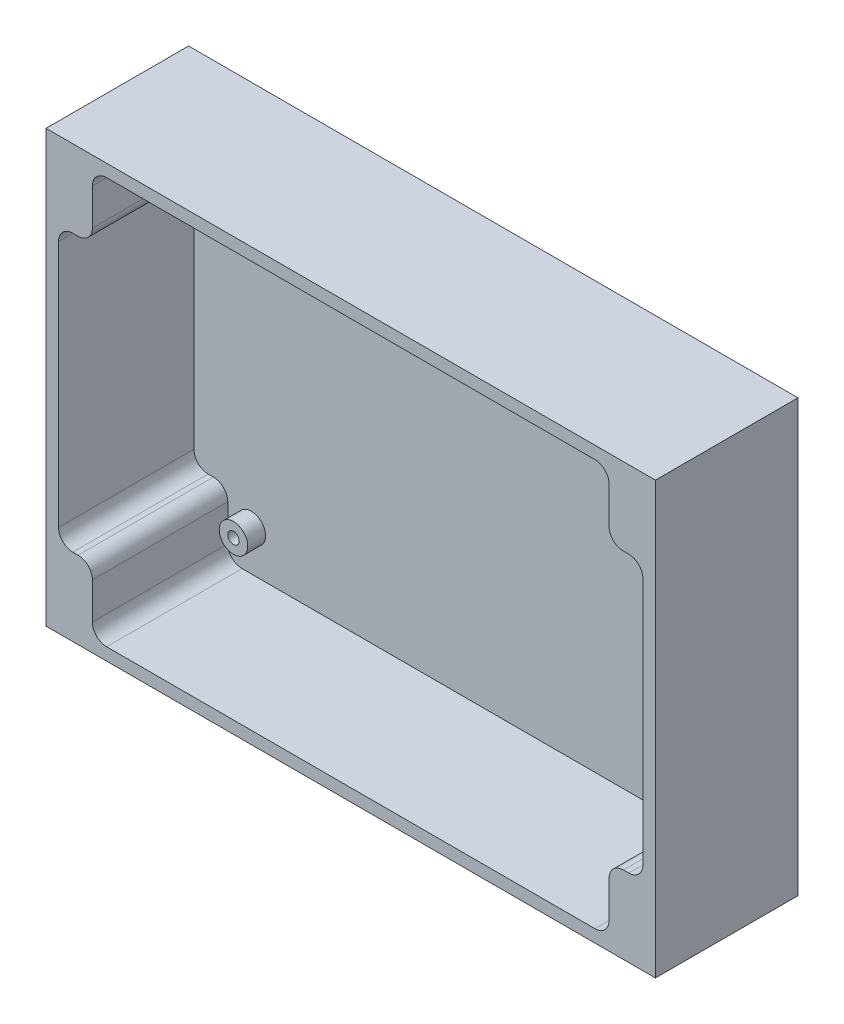
SolidWorks part; units mm, degrees
ref_plane "Спереди" through (0, 0, 0) normal (0, 0, 1) x (1, 0, 0)
ref_plane "Сверху" through (0, 0, 0) normal (0, 1, 0) x (1, 0, 0)
ref_plane "Справа" through (0, 0, 0) normal (1, 0, 0) x (0, 0, -1)
sketch "Эскиз1" plane through (0, 0, 0) normal (0, 0, 1) x (1, 0, 0)
  line L1 (-85.5, 60.5) -> (85.5, 60.5)
  line L2 (-85.5, 60.5) -> (-85.5, -60.5)
  line L3 (-85.5, -60.5) -> (85.5, -60.5)
  line L4 (85.5, 60.5) -> (85.5, -60.5)
  line L5 (-85.5, 60.5) -> (85.5, -60.5) construction
  line L6 (-85.5, -60.5) -> (85.5, 60.5) construction
  point P0 (0, 0)
  dimension "D1" = 171
  dimension "D2" = 121
extrude "Бобышка-Вытянуть1" add sketch "Эскиз1" along normal blind 40
sketch "Эскиз2" plane through (0, 0, 40) normal (0, 0, 1) x (1, 0, 0)
  line L0 (-78, 38.75) -> (-76.5, 38.75)
  line L1 (-68.5, 57) -> (68.5, 57)
  line L2 (-82, 34.75) -> (-82, -34.75)
  line L3 (-68.5, -57) -> (68.5, -57)
  line L4 (82, 34.75) -> (82, -34.75)
  line L5 (-82, 57) -> (82, -57) construction
  line L6 (-82, -57) -> (82, 57) construction
  line L7 (-72.5, 42.75) -> (-72.5, 53)
  line L8 (0, -86.6173) -> (0, 105.5743) construction
  line L9 (-131.4605, 0) -> (92.5166, 0) construction
  line L10 (72.5, 42.75) -> (72.5, 53)
  line L11 (78, 38.75) -> (76.5, 38.75)
  line L12 (72.5, -42.75) -> (72.5, -53)
  line L13 (78, -38.75) -> (76.5, -38.75)
  line L14 (-72.5, -42.75) -> (-72.5, -53)
  line L15 (-78, -38.75) -> (-76.5, -38.75)
  arc A0 (72.5, -53) -> (68.5, -57) centre (68.5, -53) cw
  arc A1 (-78, -38.75) -> (-82, -34.75) centre (-78, -34.75) cw
  arc A2 (-72.5, 53) -> (-68.5, 57) centre (-68.5, 53) cw
  arc A3 (72.5, 53) -> (68.5, 57) centre (68.5, 53) ccw
  arc A4 (-78, 38.75) -> (-82, 34.75) centre (-78, 34.75) ccw
  arc A5 (-72.5, -53) -> (-68.5, -57) centre (-68.5, -53) ccw
  arc A6 (78, -38.75) -> (82, -34.75) centre (78, -34.75) ccw
  arc A7 (78, 38.75) -> (82, 34.75) centre (78, 34.75) cw
  arc A8 (72.5, 42.75) -> (76.5, 38.75) centre (76.5, 42.75) ccw
  arc A9 (72.5, -42.75) -> (76.5, -38.75) centre (76.5, -42.75) cw
  arc A10 (-72.5, -42.75) -> (-76.5, -38.75) centre (-76.5, -42.75) ccw
  arc A11 (-76.5, 38.75) -> (-72.5, 42.75) centre (-76.5, 42.75) ccw
  point P0 (0, 0)
  point P24 (72.5, -57)
  point P27 (-82, -38.75)
  point P30 (-72.5, 57)
  point P33 (72.5, 57)
  point P36 (-82, 38.75)
  point P39 (-72.5, -57)
  point P42 (82, -38.75)
  point P45 (82, 38.75)
  point P48 (72.5, 38.75)
  point P51 (72.5, -38.75)
  point P54 (-72.5, -38.75)
  point P57 (-72.5, 38.75)
  dimension "D5" = 4
  dimension "D1" = 164
  dimension "D2" = 114
  dimension "D3" = 145
  dimension "D4" = 77.5
extrude "Вырез-Вытянуть1" cut sketch "Эскиз2" against normal blind 38
sketch "Эскиз3" plane through (0, 0, 2) normal (0, 0, 1) x (1, 0, 0)
  line L0 (0, -86.3671) -> (0, 89.4471) construction
  line L1 (-107.0781, 0) -> (123.3654, 0) construction
  circle A0 centre (-65.9, 45.75) radius 4
  circle A1 centre (65.9, 45.75) radius 4
  circle A2 centre (65.9, -45.75) radius 4
  circle A3 centre (-65.9, -45.75) radius 4
  circle A4 centre (-65.9, 45.75) radius 1.6
  circle A5 centre (65.9, 45.75) radius 1.6
  circle A6 centre (65.9, -45.75) radius 1.6
  circle A7 centre (-65.9, -45.75) radius 1.6
  circle A8 centre (55.9, -45.75) radius 4
  circle A9 centre (55.9, -45.75) radius 1.6
  circle A10 centre (55.9, 45.75) radius 4
  circle A11 centre (55.9, 45.75) radius 1.6
  dimension "D1" = 8
  dimension "D4" = 3.2
  dimension "D5" = 2
  dimension "D2" = 131.8
  dimension "D3" = 91.5
extrude "Бобышка-Вытянуть3" add sketch "Эскиз3" along normal blind 5
